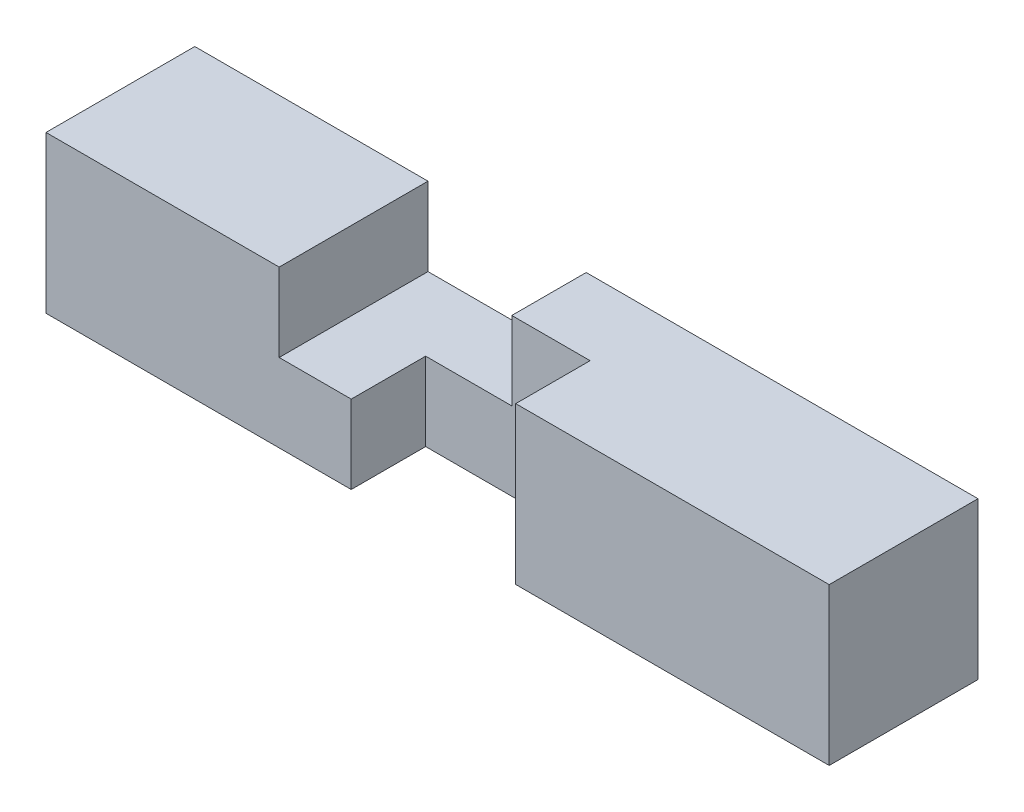
SolidWorks part; units mm, degrees
ref_plane "前基準面" through (0, 0, 0) normal (0, 0, 1) x (1, 0, 0)
ref_plane "上基準面" through (0, 0, 0) normal (0, 1, 0) x (1, 0, 0)
ref_plane "右基準面" through (0, 0, 0) normal (1, 0, 0) x (0, 0, -1)
sketch "草圖1" plane through (0, 0, 0) normal (0, 0, 1) x (1, 0, 0)
  line L1 (-50, 10) -> (50, 10)
  line L2 (-50, 10) -> (-50, -10)
  line L3 (-50, -10) -> (50, -10)
  line L4 (50, 10) -> (50, -10)
  line L5 (0, -10) -> (0, 10) construction
  line L6 (-50, 0) -> (50, 0) construction
  point P0 (0, 0)
extrude "填料-伸長1" add sketch "草圖1" along normal blind 19
sketch "草圖2" plane through (0, 10, 0) normal (0, 1, 0) x (1, 0, 0)
  line L0 (0, 0) -> (0, -19) construction
  line L1 (50, 0) -> (-50, 0) construction
  line L2 (50, -19) -> (-50, -19) construction
  line L3 (-50, -9.5) -> (50, -9.5) construction
  line L4 (-50, -19) -> (-50, 0) construction
  line L5 (50, -19) -> (50, 0) construction
  line L6 (19.9743, -10) -> (19.9743, -19)
  line L11 (0, -10) -> (0, -30) construction
  line L12 (19.9743, -19) -> (-20, -19) construction
  line L17 (19.9743, -10) -> (-10.0257, -10)
  line L19 (19.9743, -19) -> (-10.0257, -19)
  line L20 (-10.0257, -10) -> (-10.0257, -19)
extrude "除料-伸長8" cut sketch "草圖2" against normal blind 36.5
sketch "草圖7" plane through (0, 10, 0) normal (0, 1, 0) x (1, 0, 0)
  line L0 (50, 0) -> (-50, 0) construction
  line L1 (-10.0257, -19) -> (-21.0257, -19)
  line L2 (-10.0257, -19) -> (-10.0257, 0)
  line L3 (-10.0257, 0) -> (-21.0257, 0)
  line L4 (-21.0257, -19) -> (-21.0257, 0)
extrude "除料-伸長9" cut sketch "草圖7" against normal blind 10
sketch "草圖8" plane through (0, 10, 0) normal (0, 1, 0) x (1, 0, 0)
  line L0 (19.9743, -10) -> (-10.0257, -10) construction
  line L2 (-10.0257, 0) -> (9.9743, 0)
  line L3 (-10.0257, 0) -> (-10.0257, -10)
  line L4 (-10.0257, -10) -> (9.9743, -10)
  line L5 (9.9743, 0) -> (9.9743, -10)
extrude "除料-伸長10" cut sketch "草圖8" against normal blind 10
sketch "草圖9" plane through (0, 0, 0) normal (0, 1, 0) x (1, 0, 0)
  line L1 (-10.0257, -19) -> (-21.0257, -19)
  line L2 (-10.0257, -19) -> (-10.0257, 0)
  line L3 (-10.0257, 0) -> (-21.0257, 0)
  line L4 (-21.0257, -19) -> (-21.0257, 0)
extrude "填料-伸長3" add sketch "草圖9" along normal blind 10
sketch "草圖10" plane through (-10.0257, 0, 0) normal (1, 0, 0) x (0, 0, -1)
  line L2 (-10, 0) -> (-20, 0)
  line L3 (-10, 0) -> (-10, -10)
  line L4 (-10, -10) -> (-20, -10)
  line L5 (-20, 0) -> (-20, -10)
extrude "填料-伸長4" add sketch "草圖10" along normal blind 10
sketch "草圖11" plane through (0, 10, 0) normal (0, 1, 0) x (1, 0, 0)
  line L1 (9.9743, 0) -> (19.9743, 0)
  line L2 (9.9743, 0) -> (9.9743, -10)
  line L3 (9.9743, -10) -> (19.9743, -10)
  line L4 (19.9743, 0) -> (19.9743, -10)
extrude "除料-伸長11" cut sketch "草圖11" against normal blind 10
sketch "草圖12" plane through (0, 10, 0) normal (0, 1, 0) x (1, 0, 0)
  line L1 (19.9743, -19) -> (29.9743, -19)
  line L2 (19.9743, -19) -> (19.9743, -10)
  line L3 (19.9743, -10) -> (29.9743, -10)
  line L4 (29.9743, -19) -> (29.9743, -10)
sketch "草圖16" plane through (19.9743, 0, 0) normal (-1, 0, 0) x (0, 0, 1)
  line L1 (10, -10) -> (19, -10)
  line L2 (10, -10) -> (10, 10)
  line L3 (10, 10) -> (19, 10)
  line L4 (19, -10) -> (19, 10)
extrude "填料-伸長8" add sketch "草圖16" along normal blind 10
sketch "草圖17" plane through (19.9743, 0, 0) normal (-1, 0, 0) x (0, 0, 1)
  line L1 (0, 0) -> (10, 0)
  line L2 (0, 0) -> (0, 10)
  line L3 (0, 10) -> (10, 10)
  line L4 (10, 0) -> (10, 10)
extrude "填料-伸長9" add sketch "草圖17" along normal blind 20
sketch "草圖19" plane through (0, 10, 0) normal (0, 1, 0) x (1, 0, 0)
  line L0 (-10.0257, -19) -> (-50, -19) construction
  line L1 (-10.0257, 0) -> (-20.2257, 0)
  line L2 (-10.0257, 0) -> (-10.0257, -19)
  line L3 (-10.0257, -19) -> (-20.2257, -19)
  line L4 (-20.2257, 0) -> (-20.2257, -19)
extrude "除料-伸長12" cut sketch "草圖12" against normal blind 21
sketch "草圖13" plane through (29.9743, 0, 0) normal (-1, 0, 0) x (0, 0, 1)
extrude "除料-伸長16" cut sketch "草圖19" against normal blind 10
sketch "草圖20" plane through (29.9743, 0, 0) normal (-1, 0, 0) x (0, 0, 1)
  line L1 (10, 10) -> (19, 10)
  line L2 (10, 10) -> (10, -10)
  line L3 (10, -10) -> (19, -10)
  line L4 (19, 10) -> (19, -10)
extrude "填料-伸長10" add sketch "草圖20" along normal blind 10
sketch "草圖21" plane through (0, 0, 0) normal (0, 1, 0) x (1, 0, 0)
  line L0 (-20.2257, -9.5) -> (-0.0257, -9.5) construction
  line L2 (-20.2257, 0) -> (-20.2257, -19) construction
  line L3 (-0.0257, 0) -> (-0.0257, -10) construction
  line L5 (-0.0257, -20) -> (-11.0257, -20)
  line L6 (-0.0257, -20) -> (-0.0257, -9.5)
  line L7 (-0.0257, -9.5) -> (-11.0257, -9.5)
  line L8 (-11.0257, -20) -> (-11.0257, -9.5)
extrude "除料-伸長17" cut sketch "草圖21" against normal blind 10
sketch "草圖22" plane through (-0.0257, 0, 0) normal (-1, 0, 0) x (0, 0, 1)
  line L1 (9.5, -10) -> (10, -10)
  line L2 (9.5, -10) -> (9.5, 10)
  line L3 (9.5, 10) -> (10, 10)
  line L4 (10, -10) -> (10, 10)
extrude "除料-伸長18" cut sketch "草圖22" against normal blind 10
shell "薄殼1" thickness 2
sketch "草圖23" plane through (50, 0, 0) normal (1, 0, 0) x (0, 0, -1)
  line L1 (-17, 8) -> (-2, 8)
  line L2 (-17, 8) -> (-17, -8)
  line L3 (-17, -8) -> (-2, -8)
  line L4 (-2, 8) -> (-2, -8)
extrude "填料-伸長11" add sketch "草圖23" against normal blind 2
